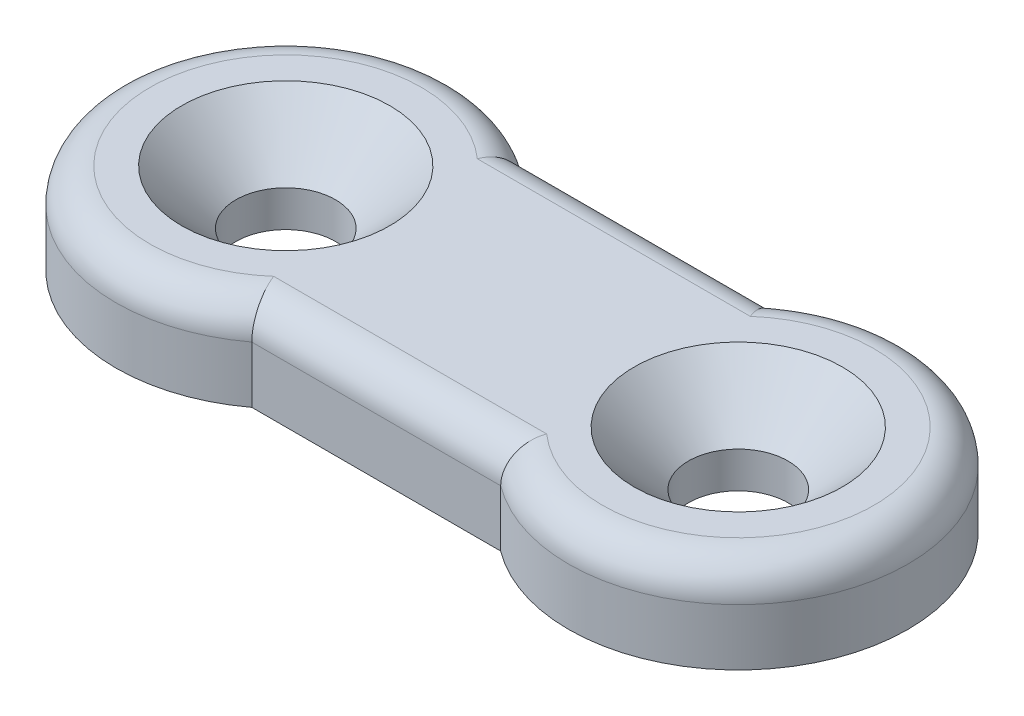
SolidWorks part; units mm, degrees
ref_plane "Front Plane" through (0, 0, 0) normal (0, 0, 1) x (1, 0, 0)
ref_plane "Top Plane" through (0, 0, 0) normal (0, 1, 0) x (1, 0, 0)
ref_plane "Right Plane" through (0, 0, 0) normal (1, 0, 0) x (0, 0, -1)
sketch "Sketch1" plane through (0, 0, 0) normal (0, 1, 0) x (1, 0, 0)
  line L0 (-5, 0) -> (5, 0) construction
  line L1 (-5, 3) -> (5, 3)
  line L2 (-5, -3) -> (5, -3)
  arc A0 (-5, 3) -> (-5, -3) centre (-5, 0) ccw
  arc A1 (5, -3) -> (5, 3) centre (5, 0) ccw
  circle A2 centre (-5, 0) radius 1.1
  circle A5 centre (5, 0) radius 1.1
  point P2 (0, 0)
  dimension "D1" = 2.2
  dimension "D2" = 10
  dimension "D3" = 6
extrude "Boss-Extrude1" add sketch "Sketch1" along normal blind 2
sketch "Sketch3" plane through (0, 2, 0) normal (0, 1, 0) x (1, 0, 0)
  circle A0 centre (-5, 0) radius 3.75
  circle A1 centre (5, 0) radius 3.75
  circle A2 centre (-5, 0) radius 1.1
  circle A3 centre (5, 0) radius 1.1
  circle A4 centre (-5, 0) radius 1.1 construction
  circle A5 centre (5, 0) radius 1.1 construction
  dimension "D1" = 7.5
extrude "Boss-Extrude3" add sketch "Sketch3" against normal up to surface (2 mm away) up to face at (0, 0, 0)
chamfer "Chamfer1" distance 1.2 angle 45 2 edges at (5, 2, 1.1) (-5, 2, 1.1)
fillet "Fillet1" radius 0.75 4 edges at (0, 2, 3) (8.75, 2, 0) (-8.75, 2, 0) (0, 2, -3)
sketch "Sketch4" plane through (0, 2, 0) normal (0, 1, 0) x (1, 0, 0)
  circle A1 centre (-5, 0) radius 2.3 construction
  circle A2 centre (-5, 0) radius 2.3 construction
  point P0 (0, 0)
  point P6 (0, 0)
  dimension "D1" = 4.6
